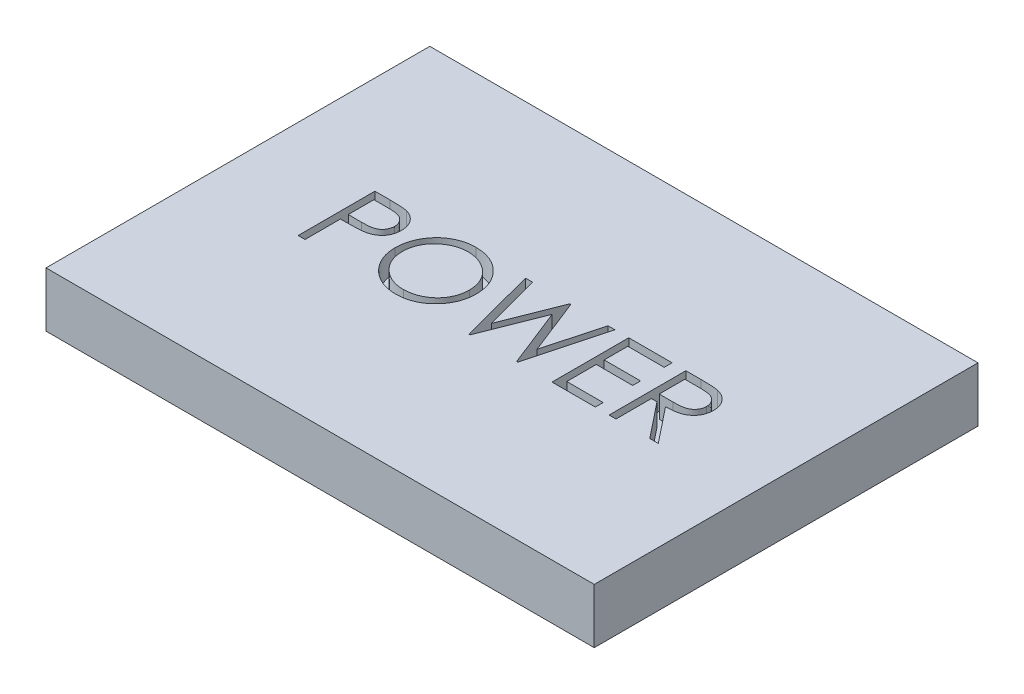
SolidWorks part; units mm, degrees
ref_plane "Alzado" through (0, 0, 0) normal (0, 0, 1) x (1, 0, 0)
ref_plane "Planta" through (0, 0, 0) normal (0, 1, 0) x (1, 0, 0)
ref_plane "Vista lateral" through (0, 0, 0) normal (1, 0, 0) x (0, 0, -1)
sketch "Croquis1" plane through (0, 0, 0) normal (0, 1, 0) x (1, 0, 0)
  line L1 (-25, -17.5) -> (25, -17.5)
  line L2 (-25, -17.5) -> (-25, 17.5)
  line L3 (-25, 17.5) -> (25, 17.5)
  line L4 (25, -17.5) -> (25, 17.5)
  line L5 (-25, -17.5) -> (25, 17.5) construction
  line L6 (-25, 17.5) -> (25, -17.5) construction
  point P0 (0, 0)
  dimension "D1" = 50
  dimension "D2" = 35
extrude "Saliente-Extruir1" add sketch "Croquis1" along normal mid plane 5
sketch "Croquis2" plane through (0, 2.5, 0) normal (0, 1, 0) x (1, 0, 0)
  text T0 "POWER" font "Century Gothic" height 7
extrude "Cortar-Extruir1" cut sketch "Croquis2" against normal blind 2 and the other way through all
